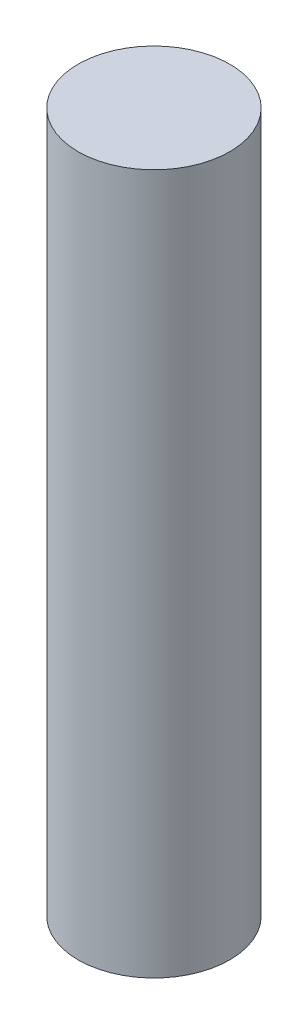
SolidWorks part; units mm, degrees
ref_plane "Front Plane" through (0, 0, 0) normal (0, 0, 1) x (1, 0, 0)
ref_plane "Top Plane" through (0, 0, 0) normal (0, 1, 0) x (1, 0, 0)
ref_plane "Right Plane" through (0, 0, 0) normal (1, 0, 0) x (0, 0, -1)
sketch "Sketch1" plane through (0, 0, 0) normal (0, 1, 0) x (1, 0, 0)
  circle A0 centre (0, 0) radius 3.25
  dimension "D1" = 6.5
extrude "Boss-Extrude1" add sketch "Sketch1" along normal blind 30
